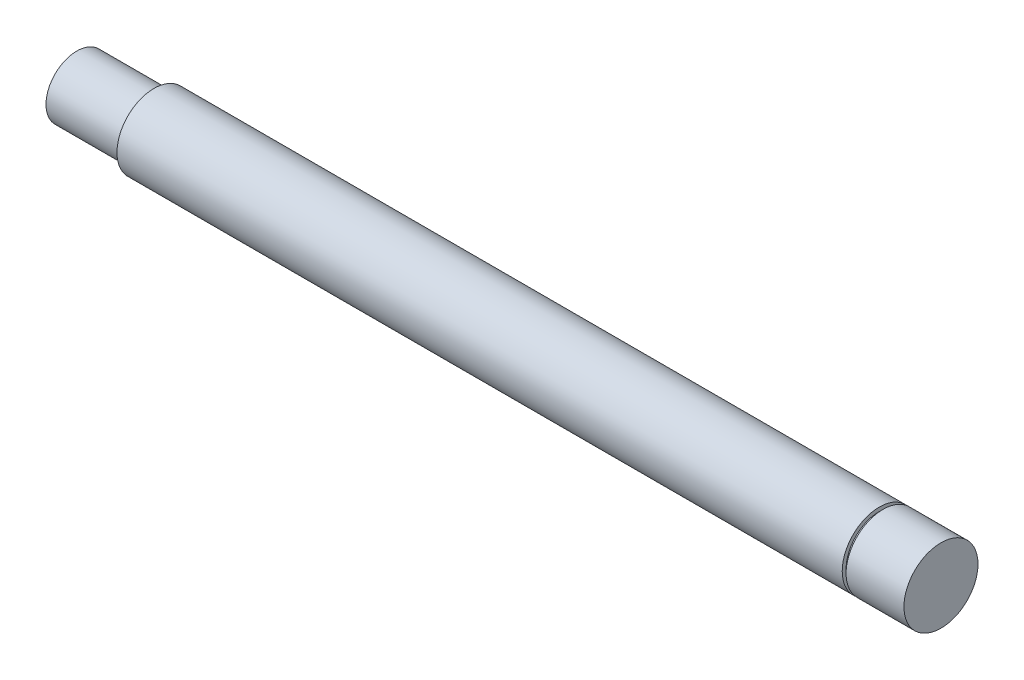
SolidWorks part; units mm, degrees
material "PW20:29:Sc:0:"
ref_plane "Front" through (0, 0, 0) normal (0, 0, 1) x (1, 0, 0)
ref_plane "Top" through (0, 0, 0) normal (0, 1, 0) x (1, 0, 0)
ref_plane "Right" through (0, 0, 0) normal (1, 0, 0) x (0, 0, -1)
other "Configuration Table"
sketch "Sketch1" plane through (0, 0, 0) normal (1, 0, 0) x (0, 0, -1)
  circle A0 centre (0, 0) radius 7.62
  dimension "D1" = 15.24
extrude "Base-Extrude" add sketch "Sketch1" along normal blind 177.8
ref_plane "Plane4" through (165.8937, 0, 0) normal (1, 0, 0) x (0, 0, -1)
sketch "Sketch2" plane through (165.8937, 0, 0) normal (1, 0, 0) x (0, 0, -1)
  circle A1 centre (0, 0) radius 6.8262
  circle A2 centre (0, 0) radius 6.8262
  circle A3 centre (0, 0) radius 7.62
  circle A4 centre (0, 0) radius 7.62
  dimension "D1" = 0.7937
  dimension "D2" = 0
extrude "Cut-Extrude1" cut sketch "Sketch2" against normal blind 0.7937
sketch "Sketch3" plane through (0, 0, 0) normal (-1, 0, 0) x (0, 0, 1)
  circle A0 centre (0, 0) radius 7.62 construction
  circle A1 centre (0, 0) radius 6.35
  circle A2 centre (0, 0) radius 6.35
  circle A3 centre (0, 0) radius 7.62
  dimension "D1" = 1.27
extrude "Cut-Extrude2" cut sketch "Sketch3" against normal blind 15.875
